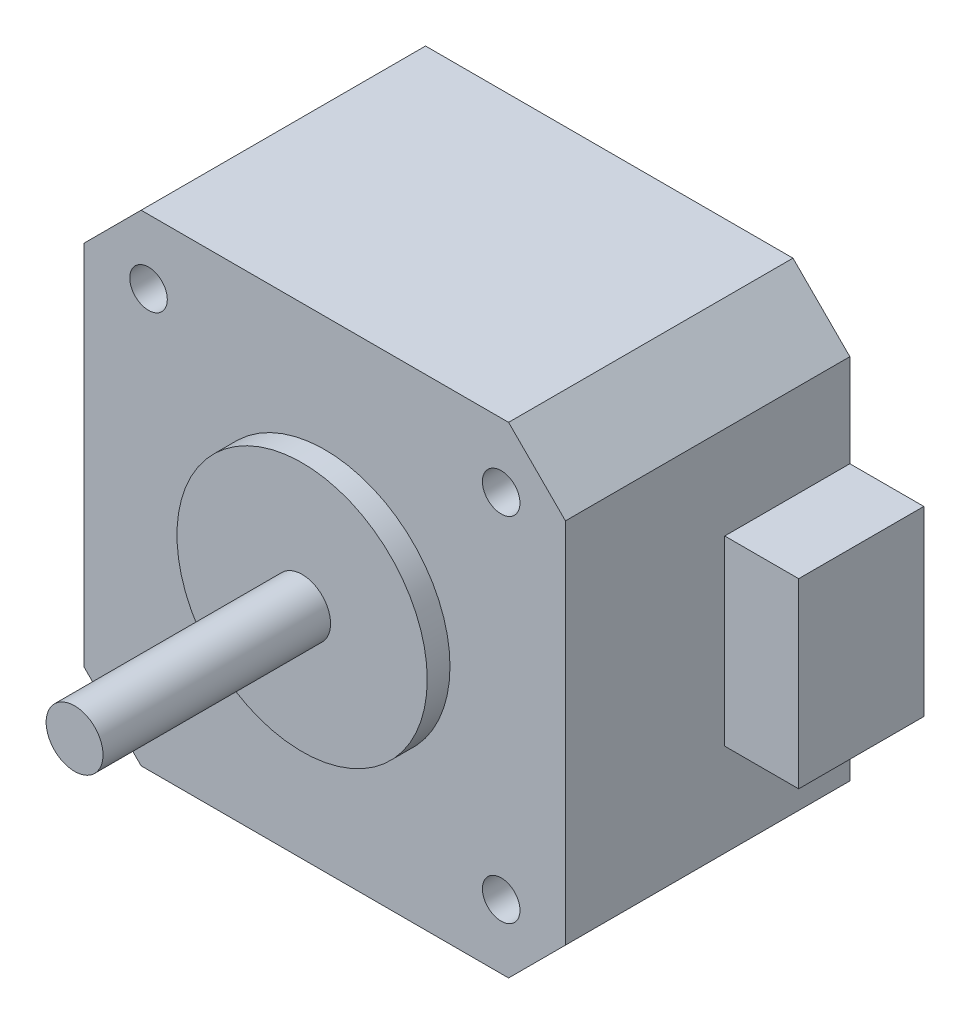
SolidWorks part; units mm, degrees
ref_plane "Front Plane" through (0, 0, 0) normal (0, 0, 1) x (1, 0, 0)
ref_plane "Top Plane" through (0, 0, 0) normal (0, 1, 0) x (1, 0, 0)
ref_plane "Right Plane" through (0, 0, 0) normal (1, 0, 0) x (0, 0, -1)
sketch "Sketch1" plane through (0, 0, 0) normal (0, 0, 1) x (1, 0, 0)
  line L1 (-21.15, -21.15) -> (21.15, -21.15)
  line L2 (-21.15, -21.15) -> (-21.15, 21.15)
  line L3 (-21.15, 21.15) -> (21.15, 21.15)
  line L4 (21.15, -21.15) -> (21.15, 21.15)
  line L5 (-21.15, -21.15) -> (21.15, 21.15) construction
  line L6 (-21.15, 21.15) -> (21.15, -21.15) construction
  point P0 (0, 0)
  dimension "D1" = 42.3
extrude "Boss-Extrude1" add sketch "Sketch1" along normal blind 25
chamfer "Chamfer1" distance 5 angle 45 4 edges at (-21.15, -21.15, 12.5) (21.15, -21.15, 12.5) (21.15, 21.15, 12.5) (-21.15, 21.15, 12.5)
sketch "Sketch3" plane through (0, 0, 25) normal (0, 0, 1) x (1, 0, 0)
  circle A0 centre (0, 0) radius 11
  dimension "D1" = 22
extrude "Boss-Extrude2" add sketch "Sketch3" along normal blind 2
sketch "Sketch4" plane through (0, 0, 27) normal (0, 0, 1) x (1, 0, 0)
  circle A0 centre (0, 0) radius 2.5
  dimension "D1" = 5
extrude "Boss-Extrude3" add sketch "Sketch4" along normal blind 20
hole_wizard "M4x0.7 Tapped Hole1" positions "Sketch6" profile "Sketch7" tap size "M4x0.7" standard "ANSI Metric"
sketch "Sketch6" plane through (0, 0, 25) normal (0, 0, 1) x (1, 0, 0)
  line L1 (-15.5, -15.5) -> (15.5, -15.5) construction
  line L2 (-15.5, -15.5) -> (-15.5, 15.5) construction
  line L3 (-15.5, 15.5) -> (15.5, 15.5) construction
  line L4 (15.5, -15.5) -> (15.5, 15.5) construction
  line L5 (0, -15.5) -> (0, 15.5) construction
  line L7 (-15.5, 0) -> (15.5, 0) construction
  point P0 (-15.5, -15.5)
  point P4 (15.5, 15.5)
  point P175 (-15.5, 15.5)
  point P176 (15.5, -15.5)
  dimension "D1" = 31
sketch "Sketch7" plane through (-15.5, -15.5, 25) normal (1, 0, 0) x (0, -1, 0)
  line L0 (0, 0) -> (0, 5.4914)
  line L1 (0, 5.4914) -> (1.65, 4.5)
  line L2 (1.65, 4.5) -> (1.65, 0)
  line L5 (1.65, 0) -> (0, 0)
  line L10 (0, 5.4914) -> (-1.65, 4.5) construction
  line L11 (0, -6.35) -> (0, 107.95) construction
  dimension "Tap Drill Dia." = 3.3
  dimension "Tap Drill Depth" = 4.5
  dimension "Drill Angle" = 118
cosmetic thread "Hole Thread1" parameters "D1"=8, "D2"=4
cosmetic thread "Hole Thread2" parameters "D1"=8, "D2"=4
cosmetic thread "Hole Thread3" parameters "D1"=8, "D2"=4
cosmetic thread "Hole Thread4" parameters "D1"=8, "D2"=4
sketch "Sketch5" plane through (21.15, 0, 0) normal (1, 0, 0) x (0, 0, -1)
  line L0 (0, -16.15) -> (0, 16.15) construction
  line L1 (-11, -8) -> (0, -8)
  line L2 (-11, -8) -> (-11, 8)
  line L3 (-11, 8) -> (0, 8)
  line L4 (0, -8) -> (0, 8)
  line L5 (-11, -8) -> (0, 8) construction
  line L6 (-11, 8) -> (0, -8) construction
  point P4 (-5.5, 0)
  point P7 (0, 0)
  point P8 (0, 0)
  dimension "D1" = 16
  dimension "D2" = 11
extrude "JST-XH6 Connector" add sketch "Sketch5" along normal blind 6.5 separate body
